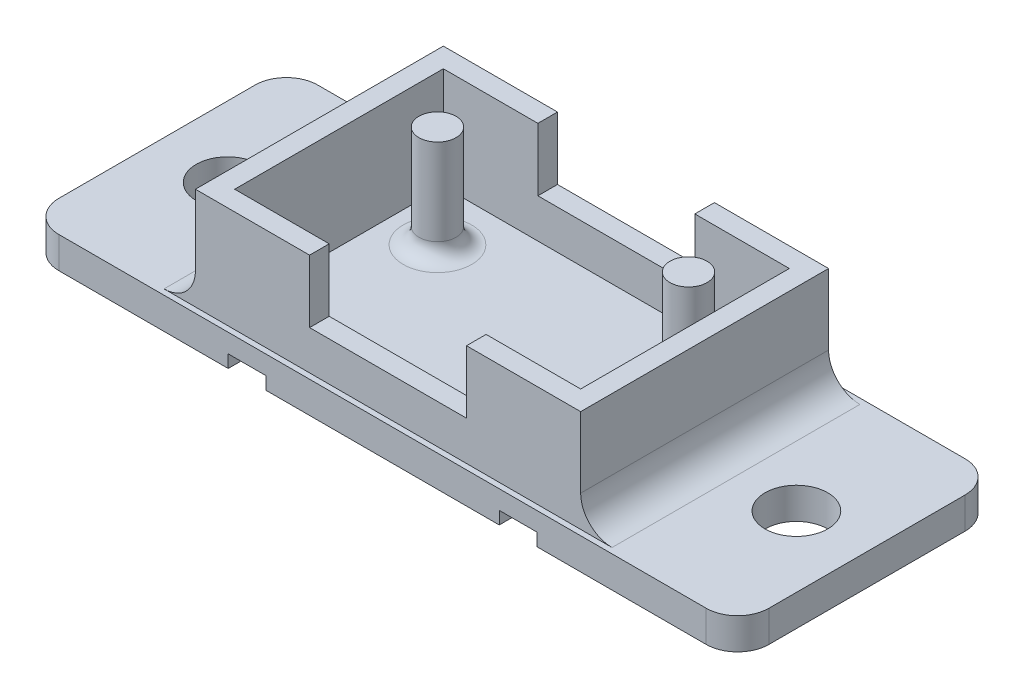
SolidWorks part; units mm, degrees
ref_plane "Front" through (0, 0, 0) normal (0, 0, 1) x (1, 0, 0)
ref_plane "Top" through (0, 0, 0) normal (0, 1, 0) x (1, 0, 0)
ref_plane "Right" through (0, 0, 0) normal (1, 0, 0) x (0, 0, -1)
sketch "Sketch1" plane through (0, 0, 0) normal (0, 1, 0) x (1, 0, 0)
  line L0 (-16.0337, -10.4775) -> (-16.0337, 10.4775)
  line L1 (-13.4937, -7.9375) -> (13.4938, -7.9375)
  line L2 (-13.4937, -7.9375) -> (-13.4937, 7.9375)
  line L3 (-13.4937, 7.9375) -> (13.4938, 7.9375)
  line L4 (13.4938, -7.9375) -> (13.4938, 7.9375)
  line L5 (-13.4937, -7.9375) -> (13.4938, 7.9375) construction
  line L6 (-13.4937, 7.9375) -> (13.4938, -7.9375) construction
  line L7 (-16.0337, 10.4775) -> (16.0338, 10.4775)
  line L8 (16.0338, -10.4775) -> (16.0338, 10.4775)
  line L9 (-16.0337, -10.4775) -> (16.0338, -10.4775)
  point P0 (0, 0)
  dimension "D1" = 15.875
  dimension "D2" = 26.9875
  dimension "D3" = 2.54
extrude "Boss-Extrude2" add sketch "Sketch1" along normal blind 2.54 contours L0 L7 L8 L9
sketch "Sketch3" plane through (0, 2.54, 0) normal (0, 1, 0) x (1, 0, 0)
  line L8 (-14.0017, -8.4455) -> (14.0018, -8.4455)
  line L9 (14.0018, -8.4455) -> (14.0018, 8.4455)
  line L10 (14.0018, 8.4455) -> (-14.0017, 8.4455)
  line L11 (-14.0017, 8.4455) -> (-14.0017, -8.4455)
  line L12 (-14.0017, -8.4455) -> (14.0018, -8.4455)
  line L13 (14.0018, -8.4455) -> (14.0018, 8.4455)
  line L14 (14.0018, 8.4455) -> (-14.0017, 8.4455)
  line L15 (-14.0017, 8.4455) -> (-14.0017, -8.4455)
  dimension "D1" = 2.032
extrude "Extrude-Thin1" add sketch "Sketch3" along normal blind 8.255 thin
sketch "Sketch4" plane through (0, 0, -10.4775) normal (0, 0, -1) x (-1, 0, 0)
  line L0 (-15.5893, 10.795) -> (15.5892, 10.795) construction
  line L1 (-6.35, 10.795) -> (6.35, 10.795)
  line L2 (-6.35, 10.795) -> (-6.35, 5.715)
  line L3 (-6.35, 5.715) -> (6.35, 5.715)
  line L4 (6.35, 10.795) -> (6.35, 5.715)
  line L5 (-16.0338, 2.54) -> (-16.0338, 0) construction
  dimension "D1" = 5.08
  dimension "D2" = 12.7
  dimension "D3" = 9.6837
extrude "Cut-Extrude1" cut sketch "Sketch4" against normal through all both and the other way through all
sketch "Sketch5" plane through (0, 2.54, 0) normal (0, 1, 0) x (1, 0, 0)
  line L0 (14.0018, 8.4455) -> (-14.0017, 8.4455) construction
  line L2 (0, 10.4775) -> (0, -10.4775) construction
  line L3 (6.35, 10.4775) -> (-6.35, 10.4775) construction
  line L4 (6.35, -10.4775) -> (-6.35, -10.4775) construction
  circle A0 centre (-10.16, 4.1275) radius 1.5
  circle A1 centre (10.16, 4.1275) radius 1.5
  dimension "D1" = 3
  dimension "D2" = 4.318
  dimension "D3" = 20.32
extrude "Boss-Extrude3" add sketch "Sketch5" along normal blind 8.255
fillet "Fillet1" radius 1.27 2 edges at (-10.16, 2.54, -2.6275) (10.16, 2.54, -5.6275)
sketch "Sketch6" plane through (0, 0, 10.4775) normal (0, 0, 1) x (1, 0, 0)
  line L0 (-16.0337, 0) -> (16.0338, 0) construction
  line L1 (-12.4936, 0) -> (-9.4456, 0)
  line L2 (-12.4936, 0) -> (-12.4936, 1.0262)
  line L3 (-12.4936, 1.0262) -> (-9.4456, 1.0262)
  line L4 (-9.4456, 0) -> (-9.4456, 1.0262)
  line L5 (-10.9696, 10.795) -> (-10.9696, 0) construction
  line L6 (-15.5892, 10.795) -> (-6.35, 10.795) construction
  line L7 (0, 5.715) -> (0, 0) construction
  line L8 (6.35, 5.715) -> (-6.35, 5.715) construction
  line L9 (12.4936, 1.0262) -> (9.4456, 1.0262)
  line L10 (9.4456, 0) -> (9.4456, 1.0262)
  line L11 (12.4936, 0) -> (9.4456, 0)
  line L12 (12.4936, 0) -> (12.4936, 1.0262)
  point P10 (-10.9696, 0)
  dimension "D1" = 1.0262
  dimension "D2" = 3.048
extrude "Cut-Extrude2" cut sketch "Sketch6" against normal through all both and the other way through all
sketch "Sketch7" plane through (-16.0337, 0, 0) normal (-1, 0, 0) x (0, 0, 1)
  line L1 (-10.4775, 2.54) -> (10.4775, 2.54)
  line L2 (-10.4775, 2.54) -> (-10.4775, 0)
  line L3 (-10.4775, 0) -> (10.4775, 0)
  line L4 (10.4775, 2.54) -> (10.4775, 0)
extrude "Boss-Extrude4" add sketch "Sketch7" along normal blind 12.7
fillet "Fillet2" radius 2.54 2 edges at (-28.7337, 1.27, 10.4775) (-28.7337, 1.27, -10.4775)
fillet "Fillet3" radius 2.54 1 edges at (-15.5892, 2.54, 0)
sketch "Sketch8" plane through (0, 2.54, 0) normal (0, 1, 0) x (1, 0, 0)
  line L0 (-23.0187, 10.4775) -> (-23.0187, -10.4775) construction
  line L1 (-26.1937, 10.4775) -> (16.0338, 10.4775) construction
  line L2 (-26.1937, -10.4775) -> (16.0338, -10.4775) construction
  line L3 (-28.7337, -7.9375) -> (-28.7337, 7.9375) construction
  circle A0 centre (-23.0187, 0) radius 2.54
  point P10 (-22.3837, 0)
  dimension "D2" = 5.08
  dimension "D1" = 5.715
extrude "Cut-Extrude3" cut sketch "Sketch8" against normal through all both and the other way through all
mirror "Mirror2" about plane through (0, 0, 0) normal (1, 0, 0) of "Boss-Extrude4"
mirror "Mirror6" about plane through (0, 0, 0) normal (1, 0, 0) of "Cut-Extrude3"
fillet "Fillet4" radius 2.54 3 edges at (28.7337, 1.27, -10.4775) (28.7337, 1.27, 10.4775) (15.5893, 2.54, 0)
